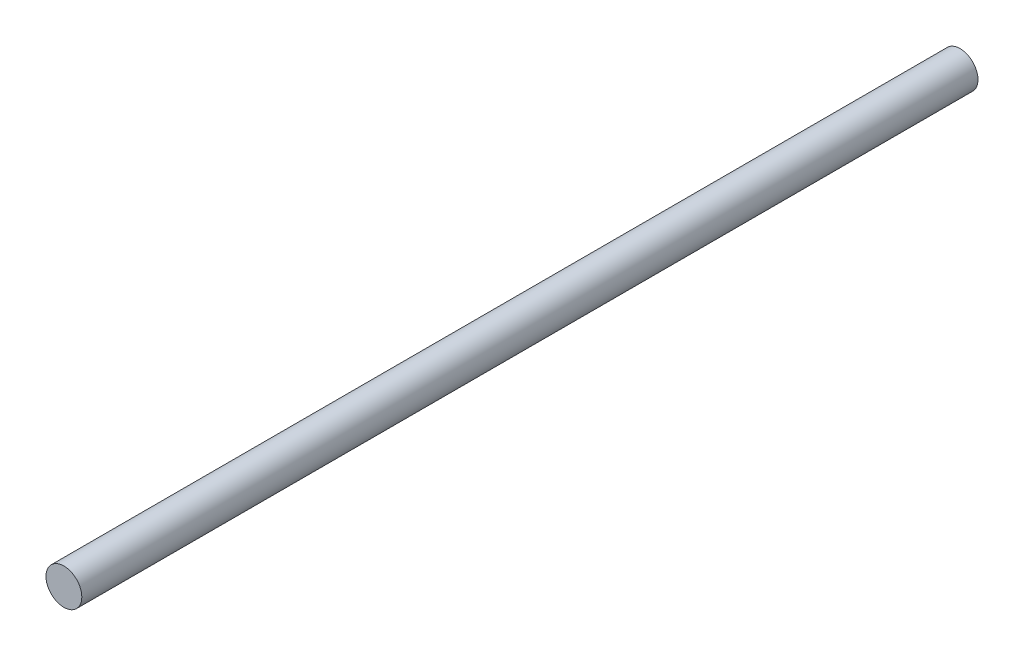
SolidWorks part; units mm, degrees
material "Polylactide (PLA)"
ref_plane "Front Plane" through (0, 0, 0) normal (0, 0, 1) x (1, 0, 0)
ref_plane "Top Plane" through (0, 0, 0) normal (0, 1, 0) x (1, 0, 0)
ref_plane "Right Plane" through (0, 0, 0) normal (1, 0, 0) x (0, 0, -1)
sketch "Sketch1" plane through (0, 0, 0) normal (0, 0, 1) x (1, 0, 0)
  circle A0 centre (125.5348, 68.0657) radius 3
extrude "Boss-Extrude1" add sketch "Sketch1" along normal blind 150 contours A0
